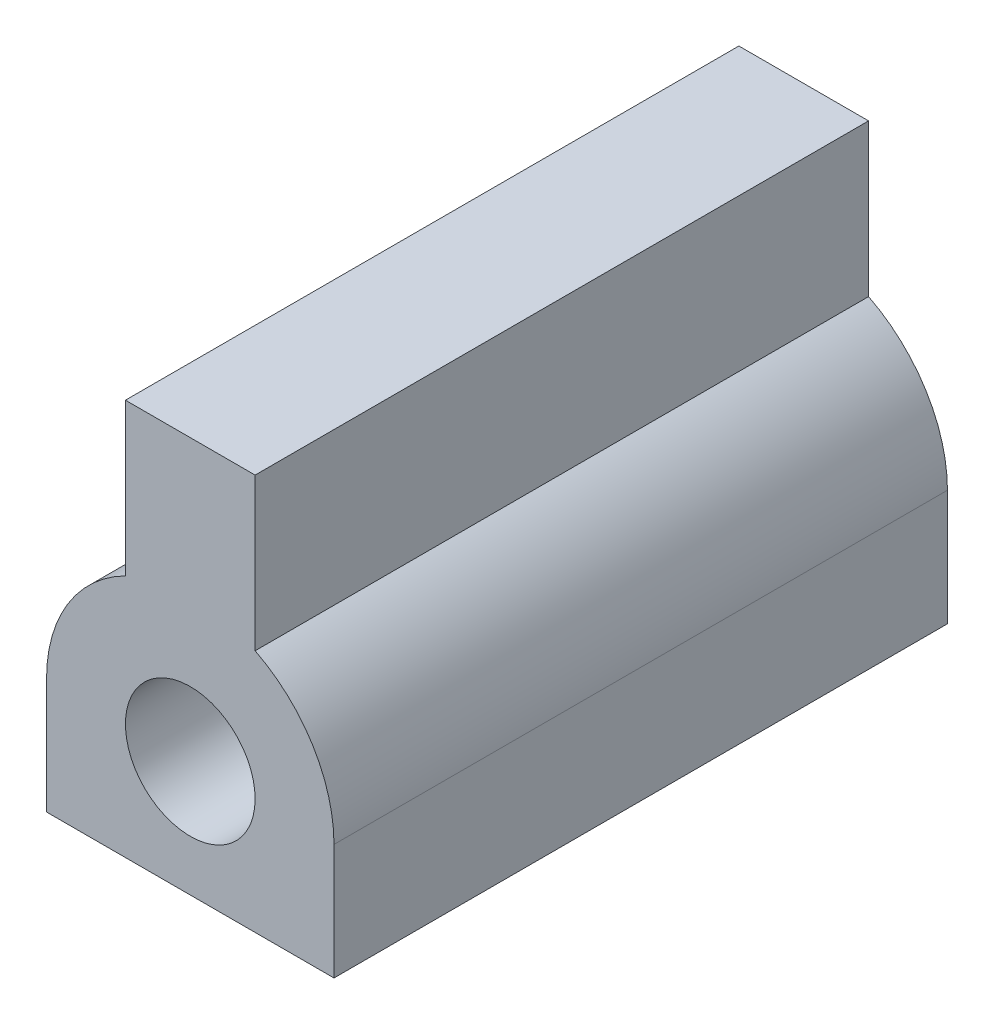
SolidWorks part; units mm, degrees
ref_plane "Front Plane" through (0, 0, 0) normal (0, 0, 1) x (1, 0, 0)
ref_plane "Top Plane" through (0, 0, 0) normal (0, 1, 0) x (1, 0, 0)
ref_plane "Right Plane" through (0, 0, 0) normal (1, 0, 0) x (0, 0, -1)
sketch "Sketch1" plane through (0, 0, 0) normal (0, 0, 1) x (1, 0, 0)
  line L0 (10.414, -8.382) -> (-10.414, -8.382)
  line L1 (-10.414, -8.382) -> (-10.414, 0)
  line L2 (10.414, 0) -> (10.414, -8.382)
  line L3 (-4.699, 9.2936) -> (-4.699, 20.32)
  line L4 (-4.699, 20.32) -> (4.699, 20.32)
  line L5 (4.699, 20.32) -> (4.699, 9.2936)
  line L6 (0, 20.32) -> (0, -8.382) construction
  arc A0 (-10.414, 0) -> (-4.699, 9.2936) centre (0, 0) cw
  circle A1 centre (0, 0) radius 4.699
  arc A2 (4.699, 9.2936) -> (10.414, 0) centre (0, 0) cw
  dimension "D1" = 9.398
  dimension "D2" = 20.828
  dimension "D3" = 28.702
  dimension "D4" = 8.382
  dimension "D5" = 9.398
extrude "Boss-Extrude1" add sketch "Sketch1" along normal mid plane 44.45
